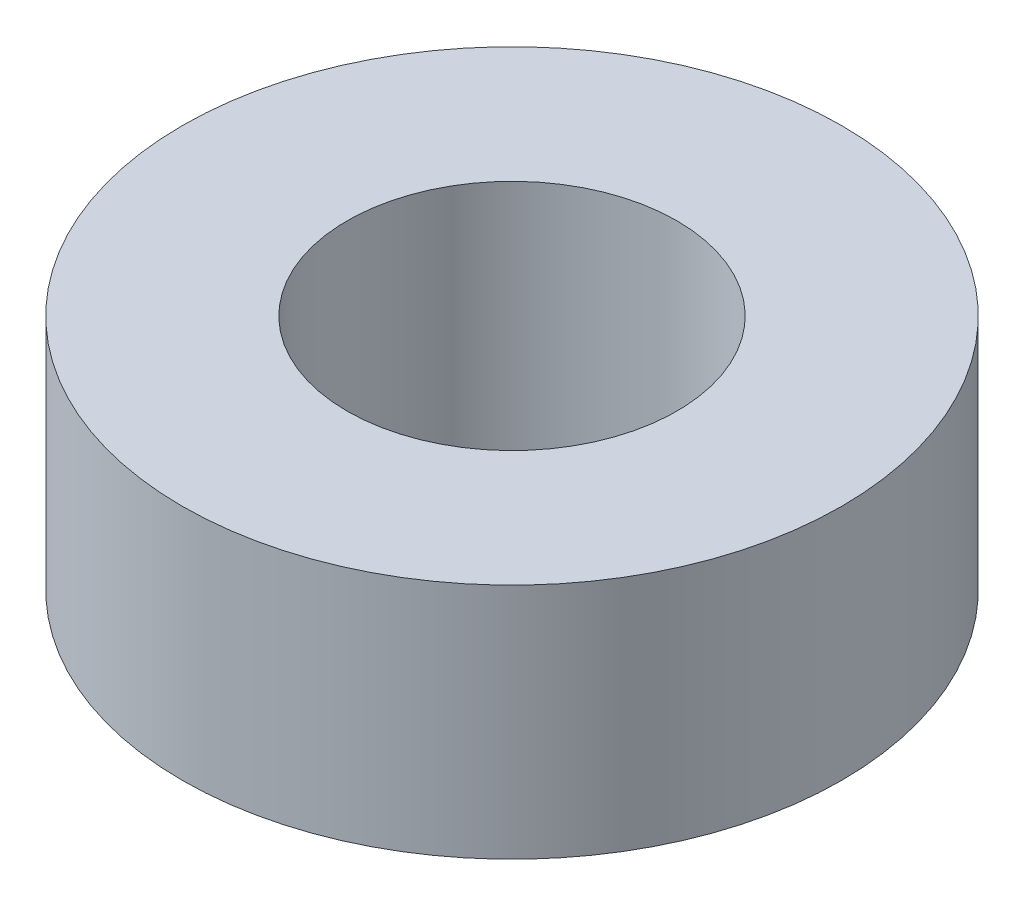
SolidWorks part; units mm, degrees
ref_plane "Front Plane" through (0, 0, 0) normal (0, 0, 1) x (1, 0, 0)
ref_plane "Top Plane" through (0, 0, 0) normal (0, 1, 0) x (1, 0, 0)
ref_plane "Right Plane" through (0, 0, 0) normal (1, 0, 0) x (0, 0, -1)
sketch "Sketch1" plane through (0, 0, 0) normal (0, 1, 0) x (1, 0, 0)
  circle A0 centre (0, 0) radius 819.15
  circle A1 centre (0, 0) radius 409.702
extrude "Boss-Extrude1" add sketch "Sketch1" along normal blind 589.788 contours A1 | A0
